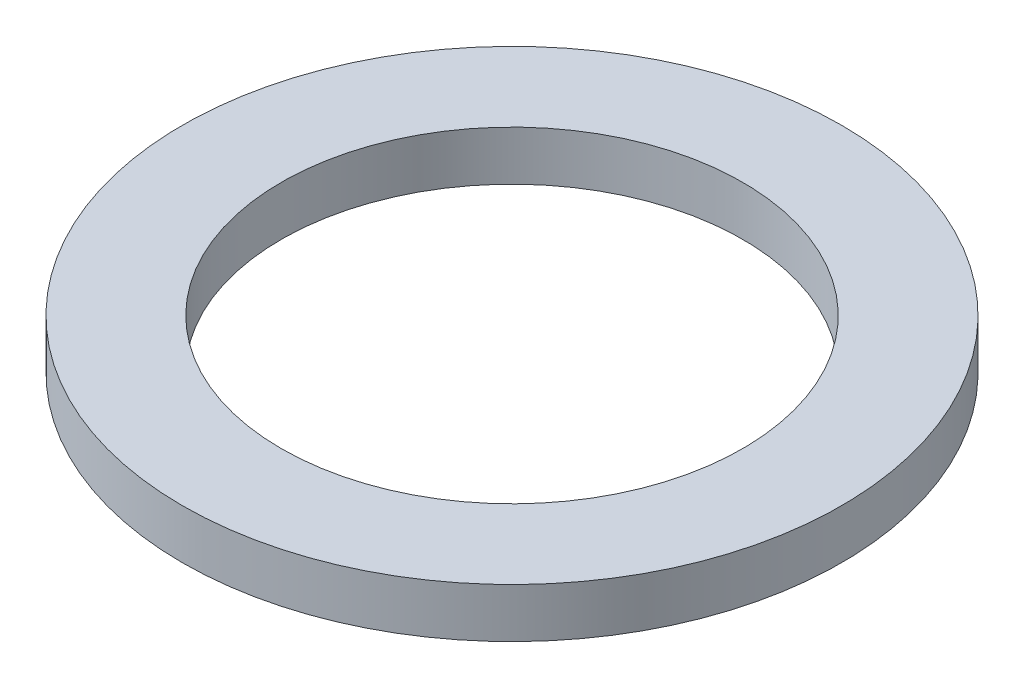
SolidWorks part; units mm, degrees
ref_plane "Front Plane" through (0, 0, 0) normal (0, 0, 1) x (1, 0, 0)
ref_plane "Top Plane" through (0, 0, 0) normal (0, 1, 0) x (1, 0, 0)
ref_plane "Right Plane" through (0, 0, 0) normal (1, 0, 0) x (0, 0, -1)
sketch "Sketch1" plane through (0, 0, 0) normal (0, 1, 0) x (1, 0, 0)
  circle A0 centre (0, 0) radius 20
  dimension "D1" = 40
extrude "Boss-Extrude1" add sketch "Sketch1" along normal blind 3
sketch "Sketch2" plane through (0, 3, 0) normal (0, 1, 0) x (1, 0, 0)
  circle A0 centre (0, 0) radius 14
  dimension "D1" = 28
extrude "Cut-Extrude1" cut sketch "Sketch2" against normal blind 3
